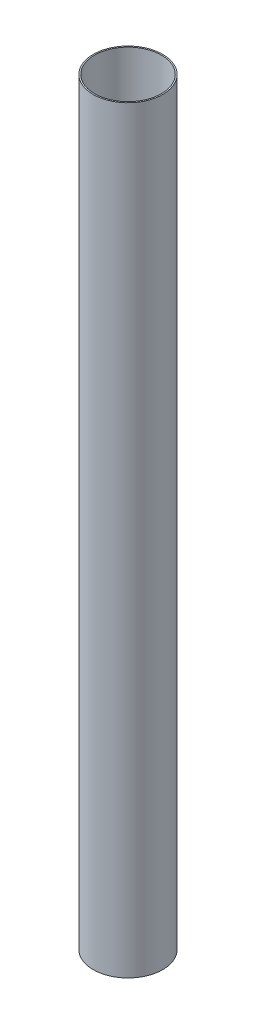
SolidWorks part; units mm, degrees
ref_plane "Front Plane" through (0, 0, 0) normal (0, 0, 1) x (1, 0, 0)
ref_plane "Top Plane" through (0, 0, 0) normal (0, 1, 0) x (1, 0, 0)
ref_plane "Right Plane" through (0, 0, 0) normal (1, 0, 0) x (0, 0, -1)
sketch "Sketch1" plane through (0, 0, 0) normal (0, 1, 0) x (1, 0, 0)
  circle A0 centre (0, 0) radius 39.624
  circle A1 centre (0, 0) radius 38.1
  dimension "D1" = 79.248
  dimension "D2" = 76.2
extrude "Boss-Extrude1" add sketch "Sketch1" along normal blind 863.6
